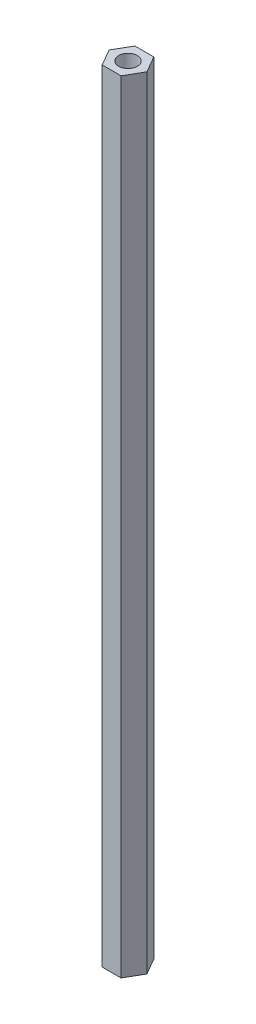
SolidWorks part; units mm, degrees
ref_plane "Front Plane" through (0, 0, 0) normal (0, 0, 1) x (1, 0, 0)
ref_plane "Top Plane" through (0, 0, 0) normal (0, 1, 0) x (1, 0, 0)
ref_plane "Right Plane" through (0, 0, 0) normal (1, 0, 0) x (0, 0, -1)
sketch "Sketch1" plane through (0, 0, 0) normal (0, 1, 0) x (1, 0, 0)
  line L1 (4.0415, 0) -> (2.0207, 3.5)
  line L2 (2.0207, 3.5) -> (-2.0207, 3.5)
  line L3 (-2.0207, 3.5) -> (-4.0415, 0)
  line L4 (-4.0415, 0) -> (-2.0207, -3.5)
  line L5 (-2.0207, -3.5) -> (2.0207, -3.5)
  line L6 (2.0207, -3.5) -> (4.0415, 0)
  circle A0 centre (0, 0) radius 3.5 construction
  circle A1 centre (0, 0) radius 2
  dimension "D1" = 4
  dimension "D2" = 7
extrude "Boss-Extrude1" add sketch "Sketch1" along normal blind 167
